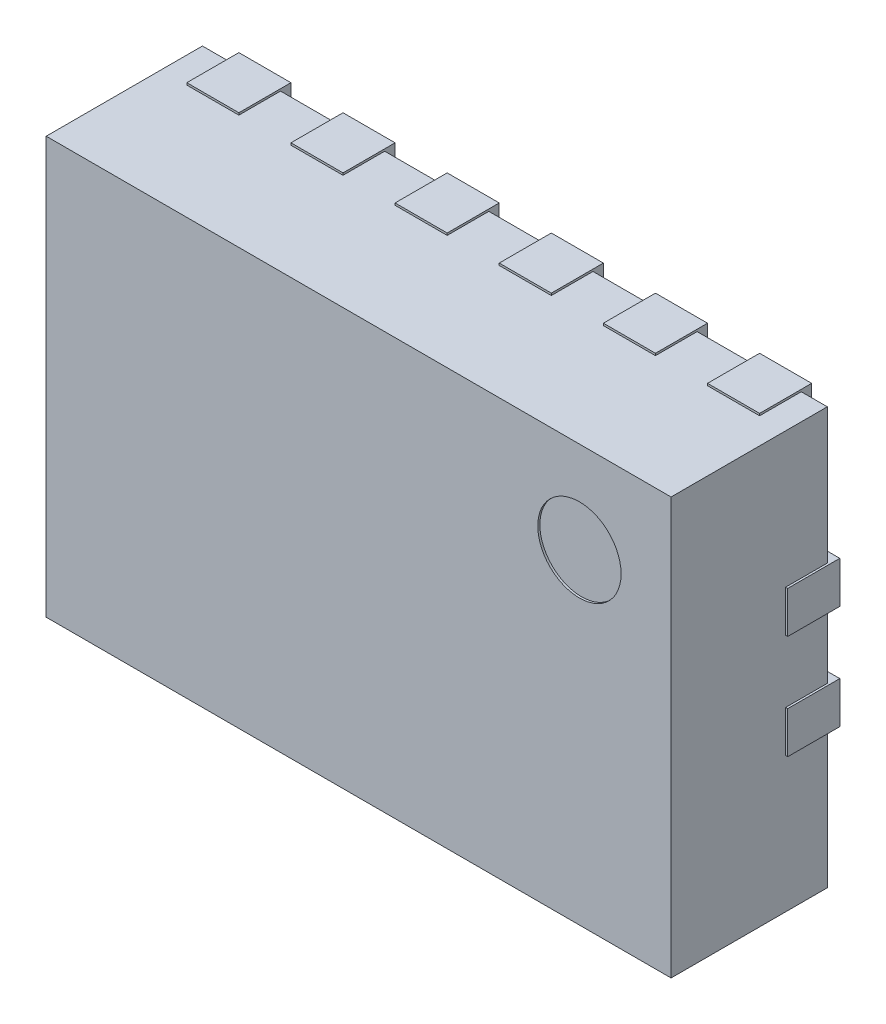
SolidWorks part; units mm, degrees
ref_plane "Front Plane" through (0, 0, 0) normal (0, 0, 1) x (1, 0, 0)
ref_plane "Top Plane" through (0, 0, 0) normal (0, 1, 0) x (1, 0, 0)
ref_plane "Right Plane" through (0, 0, 0) normal (1, 0, 0) x (0, 0, -1)
sketch "Sketch1" plane through (0, 0, 0) normal (0, 0, 1) x (1, 0, 0)
  line L1 (-1.5, 1) -> (1.5, 1)
  line L2 (-1.5, 1) -> (-1.5, -1)
  line L3 (-1.5, -1) -> (1.5, -1)
  line L4 (1.5, 1) -> (1.5, -1)
  line L5 (-1.5, 1) -> (1.5, -1) construction
  line L6 (-1.5, -1) -> (1.5, 1) construction
  point P0 (0, 0)
  dimension "D1" = 3
  dimension "D2" = 2
extrude "Boss-Extrude1" add sketch "Sketch1" along normal blind 0.75 contours L4 L3 L2 L1
sketch "Sketch2" plane through (0, 0, 0.75) normal (0, 0, 1) x (1, 0, 0)
  line L0 (1.06, 0.56) -> (1.06, 1) construction
  line L1 (-1.5, 1) -> (1.5, 1) construction
  line L2 (1.06, 0.56) -> (1.5, 0.56) construction
  line L4 (1.5, 1) -> (1.5, -1) construction
  circle A0 centre (1.06, 0.56) radius 0.2
  dimension "D1" = 0.4
  dimension "D2" = 0.44
extrude "Cut-Extrude1" cut sketch "Sketch2" against normal blind 0.01
sketch "Sketch3" plane through (0, 0, 0) normal (0, 0, -1) x (-1, 0, 0)
  line L0 (1, 0.35) -> (1.51, 0.35)
  line L1 (0.9855, -0.45) -> (-0.9855, -0.45)
  line L2 (1, -0.4355) -> (1, -0.35)
  line L3 (0.9855, 0.45) -> (-0.9855, 0.45)
  line L4 (-1, -0.4355) -> (-1, -0.35)
  line L5 (1, -0.45) -> (-1, 0.45) construction
  line L6 (1, 0.45) -> (-1, -0.45) construction
  line L7 (1.5, 1) -> (1.5, -1) construction
  line L8 (1.51, 0.35) -> (1.51, 0.15)
  line L9 (1.51, 0.15) -> (1, 0.15)
  line L10 (1, 0.15) -> (1, -0.15)
  line L11 (1, -0.15) -> (1.51, -0.15)
  line L12 (1.51, -0.15) -> (1.51, -0.35)
  line L13 (1.51, -0.35) -> (1, -0.35)
  line L14 (1, 0.35) -> (1, 0.4355)
  line L15 (-1, 0.35) -> (-1.51, 0.35)
  line L16 (-1.5, 1) -> (-1.5, -1) construction
  line L17 (-1.51, 0.35) -> (-1.51, 0.15)
  line L18 (-1.51, 0.15) -> (-1, 0.15)
  line L19 (-1, 0.15) -> (-1, -0.15)
  line L20 (-1, -0.15) -> (-1.51, -0.15)
  line L21 (-1.51, -0.15) -> (-1.51, -0.35)
  line L22 (-1.51, -0.35) -> (-1, -0.35)
  line L23 (-1, 0.35) -> (-1, 0.4355)
  line L24 (-0.8, 0.45) -> (-1, 0.25)
  arc A0 (-0.9855, -0.45) -> (-1, -0.4355) centre (-0.9855, -0.4355) cw
  arc A1 (-0.9855, 0.45) -> (-1, 0.4355) centre (-0.9855, 0.4355) ccw
  arc A2 (1, 0.4355) -> (0.9855, 0.45) centre (0.9855, 0.4355) ccw
  arc A3 (1, -0.4355) -> (0.9855, -0.45) centre (0.9855, -0.4355) cw
  point P0 (0, 0)
  point P28 (1, 0)
  point P30 (1.51, -0.25)
  point P31 (1.51, 0.25)
  point P41 (-1, 0)
  line M2 (-1.5, 1) -> (-1.5, -1)
  line M4 (1.5, -1) -> (1.5, 1)
  dimension "D3" = 0.0145
  dimension "D1" = 2
  dimension "D2" = 0.9
  dimension "D4" = 0.2
  dimension "D5" = 0.5
  dimension "D7" = 0.2
  dimension "D9" = 45
  dimension "D10" = 0.2
  dimension "D11" = 0.01
  dimension "D12" = 0.01
extrude "Boss-Extrude2" add sketch "Sketch3" along normal blind 0.05 and the other way blind 0.2 contours A3 L2 L13 L11 L10 L9 L0 L14 A2 L3 L24 L23 L15 L18 L19 L20 L22 L4 A0 L1 M4 M2 | L9 L8 L0 M4 | L13 L12 L11 M4 | L21 L22 L20 M2 | L17 L18 L15 M2
sketch "Sketch6" plane through (0, 0, 0) normal (0, 0, -1) x (-1, 0, 0)
  line L0 (-1.375, 1.01) -> (-1.125, 1.01)
  line L1 (-1.125, 1.01) -> (-1.125, 1)
  line L2 (1.5, 1) -> (-1.5, 1) construction
  line L3 (-1.125, 1) -> (-1.125, 0.825)
  line L4 (-1.375, 1.01) -> (-1.375, 1)
  line L5 (-1.375, 1) -> (-1.375, 0.825)
  arc A0 (-1.375, 0.825) -> (-1.125, 0.825) centre (-1.25, 0.825) ccw
  point P9 (-1.25, 0.7)
  dimension "D1" = 0.01
  dimension "D2" = 0.25
  dimension "D3" = 0.3
  dimension "D4" = 1.25
extrude "Boss-Extrude4" add sketch "Sketch6" along normal blind 0.05 and the other way blind 0.2
pattern_linear "LPattern2" count 6 spacing 0.5 along (-1, 0, 0) of "Boss-Extrude4"
mirror "Mirror2" about plane through (0, 0, 0) normal (0, 1, 0) of "LPattern2", "Boss-Extrude4"
equation "\"E\" = 2"
equation "\"D\"= 3"
equation "\"H\"= \"A\" + \"A1\""
equation "\"D1@Boss-Extrude1\"=\"H\""
equation "\"D2@Sketch1\"=\"E\""
equation "\"D1@Sketch1\"=\"D\""
equation "\"D2\" = 2"
equation "\"E2\" = 0.9"
equation "\"L\"=0.3"
equation "\"b\"=0.25"
equation "\"e_\"= 0.5"
equation "\"A3\"= 0.2"
equation "\"K\"= 0.2"
equation "\"A1\"= 0.05"
equation "\"D1@Sketch3\"=\"D2\""
equation "\"D2@Sketch3\"=\"E2\""
equation "\"GND_R\"= ( \"D2\" + \"E2\" ) / 2 * 0.01"
equation "\"D3@Sketch3\"=\"GND_R\""
equation "\"D1@Boss-Extrude2\"=\"A1\""
equation "\"Px\" = 6"
equation "\"Py\"= 2"
equation "\"P\"= 2 * \"Px\" + 2 * \"Py\""
equation "\"D2@Sketch6\"=\"b\""
equation "\"D3@Sketch6\"=\"L\""
equation "\"D4@Sketch6\"=(\"Px\"/2-1)*\"e_\"+\"e_\"/2"
equation "\"D1@Boss-Extrude4\"=\"A1\""
equation "\"D2@Boss-Extrude4\"=\"A3\""
equation "\"D3@LPattern2\"=\"e_\""
equation "\"D1@LPattern2\"=\"Px\""
equation "\"A\" = 0.7"
equation "\"D2@Sketch2\"=\"D1@Sketch2\"*1.1"
equation "\"e_y\"= 1.5"
equation "\"D7@Sketch3\"=\"D4@Sketch3\""
equation "\"D2@Boss-Extrude2\"=\"A3\""
equation "\"D12@Sketch3\"=\"D11@Sketch3\""
